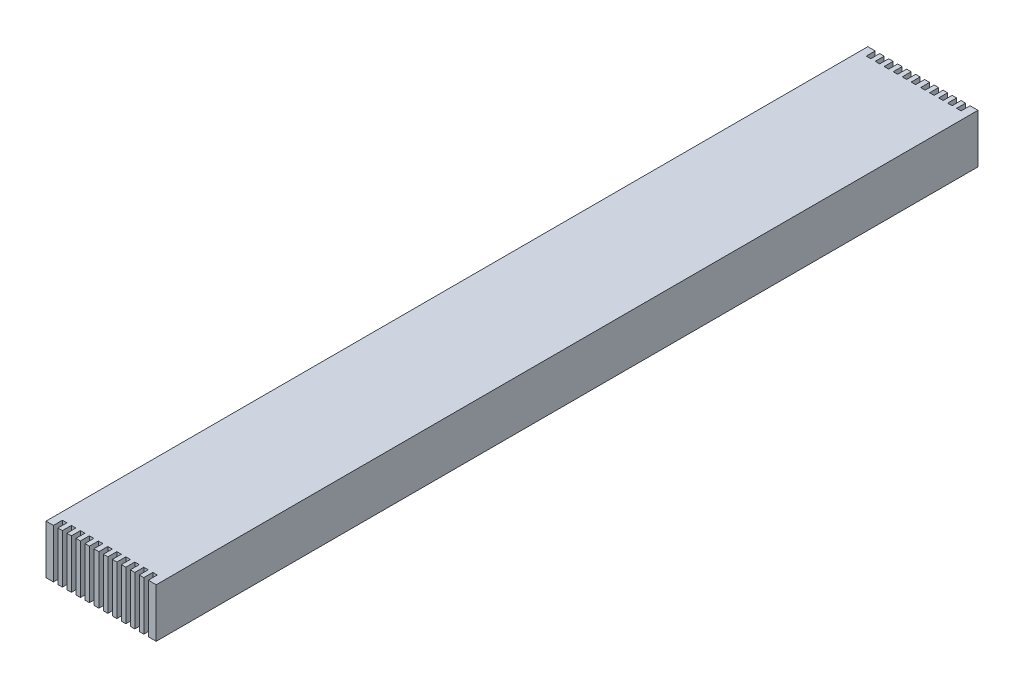
SolidWorks part; units mm, degrees
ref_plane "Front Plane" through (0, 0, 0) normal (0, 0, 1) x (1, 0, 0)
ref_plane "Top Plane" through (0, 0, 0) normal (0, 1, 0) x (1, 0, 0)
ref_plane "Right Plane" through (0, 0, 0) normal (1, 0, 0) x (0, 0, -1)
sketch "Sketch1" plane through (0, 0, 0) normal (0, 0, 1) x (1, 0, 0)
  line L0 (390.2862, -454.0022) -> (340.2862, -454.0022)
  line L1 (-347.891, 41.2406) -> (878.4633, 41.2406)
  line L2 (-347.891, 41.2406) -> (-347.891, -504.0022)
  line L3 (-347.891, -504.0022) -> (-265.3555, -504.0022)
  line L4 (878.4633, 41.2406) -> (878.4633, -504.0022)
  line L5 (340.2862, -454.0022) -> (340.2862, -504.0022)
  line L6 (290.2862, -454.0022) -> (240.2862, -454.0022)
  line L7 (240.2862, -454.0022) -> (240.2862, -504.0022)
  line L8 (290.2862, -454.0022) -> (290.2862, -504.0022)
  line L9 (390.2862, -454.0022) -> (390.2862, -504.0022)
  line L10 (490.2862, -454.0022) -> (440.2862, -454.0022)
  line L11 (440.2862, -454.0022) -> (440.2862, -504.0022)
  line L12 (490.2862, -454.0022) -> (490.2862, -504.0022)
  line L13 (590.2862, -454.0022) -> (540.2862, -454.0022)
  line L14 (540.2862, -454.0022) -> (540.2862, -504.0022)
  line L15 (690.2862, -454.0022) -> (690.2862, -504.0022)
  line L16 (590.2862, -454.0022) -> (590.2862, -504.0022)
  line L17 (690.2862, -454.0022) -> (640.2862, -454.0022)
  line L18 (640.2862, -454.0022) -> (640.2862, -504.0022)
  line L19 (184.6445, -454.0022) -> (134.6445, -454.0022)
  line L20 (790.2862, -454.0022) -> (740.2862, -454.0022)
  line L21 (740.2862, -454.0022) -> (740.2862, -504.0022)
  line L22 (-265.3555, -454.0022) -> (-265.3555, -504.0022)
  line L23 (184.6445, -454.0022) -> (184.6445, -504.0022)
  line L24 (790.2862, -454.0022) -> (790.2862, -504.0022)
  line L25 (84.6445, -454.0022) -> (34.6445, -454.0022)
  line L26 (84.6445, -454.0022) -> (84.6445, -504.0022)
  line L27 (-15.3555, -454.0022) -> (-15.3555, -504.0022)
  line L28 (134.6445, -454.0022) -> (134.6445, -504.0022)
  line L29 (-115.3555, -454.0022) -> (-115.3555, -504.0022)
  line L30 (34.6445, -454.0022) -> (34.6445, -504.0022)
  line L31 (-65.3555, -454.0022) -> (-65.3555, -504.0022)
  line L32 (-215.3555, -454.0022) -> (-265.3555, -454.0022)
  line L33 (-165.3555, -454.0022) -> (-165.3555, -504.0022)
  line L34 (-15.3555, -454.0022) -> (-65.3555, -454.0022)
  line L35 (-115.3555, -454.0022) -> (-165.3555, -454.0022)
  line L36 (-215.3555, -454.0022) -> (-215.3555, -504.0022)
  line L37 (-215.3555, -504.0022) -> (-165.3555, -504.0022)
  line L38 (-115.3555, -504.0022) -> (-65.3555, -504.0022)
  line L39 (-15.3555, -504.0022) -> (34.6445, -504.0022)
  line L40 (84.6445, -504.0022) -> (134.6445, -504.0022)
  line L41 (184.6445, -504.0022) -> (240.2862, -504.0022)
  line L42 (290.2862, -504.0022) -> (340.2862, -504.0022)
  line L43 (390.2862, -504.0022) -> (440.2862, -504.0022)
  line L44 (490.2862, -504.0022) -> (540.2862, -504.0022)
  line L45 (690.2862, -504.0022) -> (740.2862, -504.0022)
  line L46 (790.2862, -504.0022) -> (878.4633, -504.0022)
  line L47 (590.2862, -504.0022) -> (640.2862, -504.0022)
extrude "Boss-Extrude1" add sketch "Sketch1" along normal blind 9144
sketch "Sketch2" plane through (0, 0, 9144) normal (0, 0, 1) x (1, 0, 0)
  line L0 (-265.3555, -454.0022) -> (-265.3555, 201.7073)
  line L1 (-215.3555, 201.7073) -> (-165.3555, 201.7073)
  line L2 (-215.3555, 201.7073) -> (-215.3555, -454.0022)
  line L3 (-215.3555, -454.0022) -> (-265.3555, -454.0022)
  line L4 (-165.3555, 201.7073) -> (-165.3555, -454.0022)
  line L5 (-165.3555, -454.0022) -> (-115.3555, -454.0022)
  line L6 (-115.3555, -454.0022) -> (-115.3555, 201.7073)
  line L7 (-115.3555, 201.7073) -> (-65.3555, 201.7073)
  line L8 (-65.3555, 201.7073) -> (-65.3555, -454.0022)
  line L9 (-65.3555, -454.0022) -> (-15.3555, -454.0022)
  line L10 (-15.3555, -454.0022) -> (-15.3555, 201.7073)
  line L11 (-15.3555, 201.7073) -> (34.6445, 201.7073)
  line L12 (34.6445, 201.7073) -> (34.6445, -454.0022)
  line L13 (34.6445, -454.0022) -> (84.6445, -454.0022)
  line L14 (84.6445, -454.0022) -> (84.6445, 201.7073)
  line L15 (84.6445, 201.7073) -> (134.6445, 201.7073)
  line L16 (134.6445, 201.7073) -> (134.6445, -454.0022)
  line L17 (134.6445, -454.0022) -> (184.6445, -454.0022)
  line L18 (184.6445, -454.0022) -> (184.6445, 201.7073)
  line L19 (184.6445, 201.7073) -> (240.2862, 201.7073)
  line L20 (240.2862, 201.7073) -> (240.2862, -454.0022)
  line L21 (240.2862, -454.0022) -> (290.2862, -454.0022)
  line L22 (290.2862, -454.0022) -> (290.2862, 201.7073)
  line L23 (290.2862, 201.7073) -> (340.2862, 201.7073)
  line L24 (340.2862, 201.7073) -> (340.2862, -454.0022)
  line L25 (340.2862, -454.0022) -> (390.2862, -454.0022)
  line L26 (390.2862, -454.0022) -> (390.2862, 201.7073)
  line L27 (390.2862, 201.7073) -> (440.2862, 201.7073)
  line L28 (440.2862, 201.7073) -> (440.2862, -454.0022)
  line L29 (440.2862, -454.0022) -> (490.2862, -454.0022)
  line L30 (490.2862, -454.0022) -> (490.2862, 201.7073)
  line L31 (490.2862, 201.7073) -> (540.2862, 201.7073)
  line L32 (540.2862, 201.7073) -> (540.2862, -454.0022)
  line L33 (540.2862, -454.0022) -> (590.2862, -454.0022)
  line L34 (590.2862, -454.0022) -> (590.2862, 201.7073)
  line L35 (590.2862, 201.7073) -> (640.2862, 201.7073)
  line L36 (640.2862, 201.7073) -> (640.2862, -454.0022)
  line L37 (640.2862, -454.0022) -> (690.2862, -454.0022)
  line L38 (690.2862, -454.0022) -> (690.2862, 201.7073)
  line L39 (690.2862, 201.7073) -> (740.2862, 201.7073)
  line L40 (740.2862, 201.7073) -> (740.2862, -454.0022)
  line L41 (740.2862, -454.0022) -> (790.2862, -454.0022)
  line L42 (790.2862, -454.0022) -> (790.2862, 367.4342)
  line L43 (790.2862, 367.4342) -> (-265.3555, 367.4342)
  line L44 (-265.3555, 367.4342) -> (-265.3555, 201.7073)
  line L45 (790.2862, -454.0022) -> (1744.499, -200.374) construction
extrude "Cut-Extrude1" cut sketch "Sketch2" against normal blind 100
sketch "Sketch3" plane through (0, 0, 0) normal (0, 0, -1) x (-1, 0, 0)
  line L0 (-790.2862, -454.0022) -> (-790.2862, 201.7073)
  line L1 (-740.2862, 201.7073) -> (-690.2862, 201.7073)
  line L2 (-740.2862, 201.7073) -> (-740.2862, -454.0022)
  line L3 (-740.2862, -454.0022) -> (-790.2862, -454.0022)
  line L4 (-690.2862, 201.7073) -> (-690.2862, -454.0022)
  line L5 (-690.2862, -454.0022) -> (-640.2862, -454.0022)
  line L6 (-640.2862, -454.0022) -> (-640.2862, 201.7073)
  line L7 (-640.2862, 201.7073) -> (-590.2862, 201.7073)
  line L8 (-590.2862, 201.7073) -> (-590.2862, -454.0022)
  line L9 (-590.2862, -454.0022) -> (-540.2862, -454.0022)
  line L10 (-540.2862, -454.0022) -> (-540.2862, 201.7073)
  line L11 (-540.2862, 201.7073) -> (-490.2862, 201.7073)
  line L12 (-490.2862, 201.7073) -> (-490.2862, -454.0022)
  line L13 (-490.2862, -454.0022) -> (-440.2862, -454.0022)
  line L14 (-440.2862, -454.0022) -> (-440.2862, 201.7073)
  line L15 (-440.2862, 201.7073) -> (-390.2862, 201.7073)
  line L16 (-390.2862, 201.7073) -> (-390.2862, -454.0022)
  line L17 (-390.2862, -454.0022) -> (-340.2862, -454.0022)
  line L18 (-340.2862, -454.0022) -> (-340.2862, 201.7073)
  line L19 (-340.2862, 201.7073) -> (-284.6445, 201.7073)
  line L20 (-284.6445, 201.7073) -> (-284.6445, -454.0022)
  line L21 (-284.6445, -454.0022) -> (-234.6445, -454.0022)
  line L22 (-234.6445, -454.0022) -> (-234.6445, 201.7073)
  line L23 (-234.6445, 201.7073) -> (-184.6445, 201.7073)
  line L24 (-184.6445, 201.7073) -> (-184.6445, -454.0022)
  line L25 (-184.6445, -454.0022) -> (-134.6445, -454.0022)
  line L26 (-134.6445, -454.0022) -> (-134.6445, 201.7073)
  line L27 (-134.6445, 201.7073) -> (-84.6445, 201.7073)
  line L28 (-84.6445, 201.7073) -> (-84.6445, -454.0022)
  line L29 (-84.6445, -454.0022) -> (-34.6445, -454.0022)
  line L30 (-34.6445, -454.0022) -> (-34.6445, 201.7073)
  line L31 (-34.6445, 201.7073) -> (15.3555, 201.7073)
  line L32 (15.3555, 201.7073) -> (15.3555, -454.0022)
  line L33 (15.3555, -454.0022) -> (65.3555, -454.0022)
  line L34 (65.3555, -454.0022) -> (65.3555, 201.7073)
  line L35 (65.3555, 201.7073) -> (115.3555, 201.7073)
  line L36 (115.3555, 201.7073) -> (115.3555, -454.0022)
  line L37 (115.3555, -454.0022) -> (165.3555, -454.0022)
  line L38 (165.3555, -454.0022) -> (165.3555, 201.7073)
  line L39 (165.3555, 201.7073) -> (215.3555, 201.7073)
  line L40 (215.3555, 201.7073) -> (215.3555, -454.0022)
  line L41 (215.3555, -454.0022) -> (265.3555, -454.0022)
  line L42 (265.3555, -454.0022) -> (265.3555, 367.4342)
  line L43 (265.3555, 367.4342) -> (-790.2862, 367.4342)
  line L44 (-790.2862, 367.4342) -> (-790.2862, 201.7073)
extrude "Cut-Extrude2" cut sketch "Sketch3" against normal blind 100
